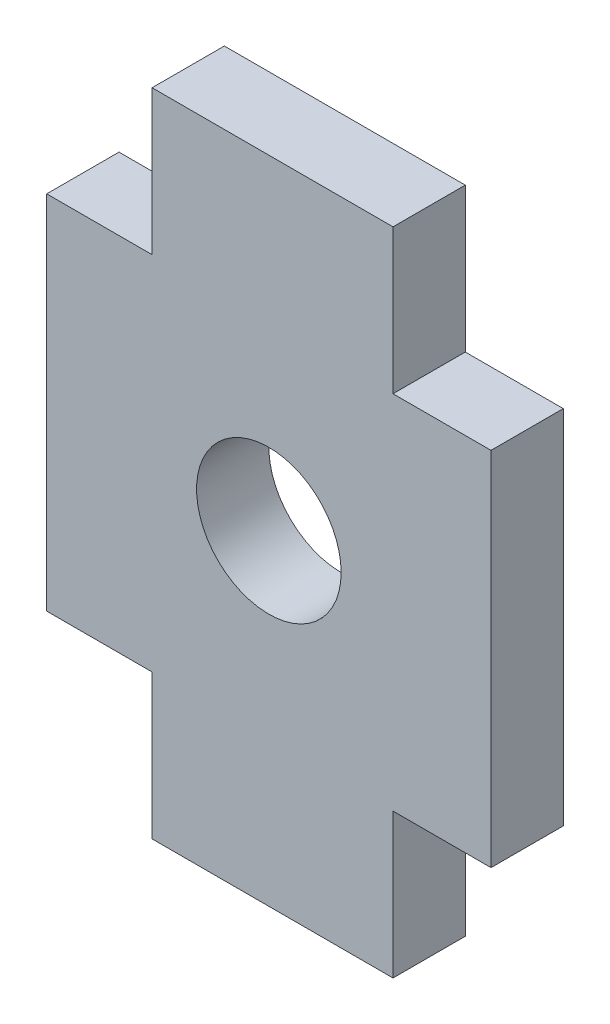
SolidWorks part; units mm, degrees
ref_plane "Front Plane" through (0, 0, 0) normal (0, 0, 1) x (1, 0, 0)
ref_plane "Top Plane" through (0, 0, 0) normal (0, 1, 0) x (1, 0, 0)
ref_plane "Right Plane" through (0, 0, 0) normal (1, 0, 0) x (0, 0, -1)
sketch "Sketch1" plane through (0, 0, 0) normal (0, 0, 1) x (1, 0, 0)
  line L2 (-211.4286, -75.763) -> (-211.4286, -105.763)
  line L4 (-174.5494, -75.763) -> (-174.5494, -105.763)
  line L6 (-202.6836, -69.763) -> (-202.6836, -63.763)
  line L7 (-202.6836, -63.763) -> (-182.6836, -63.763)
  line L8 (-182.6836, -69.763) -> (-182.6836, -63.763)
  line L14 (-211.4286, -75.763) -> (-202.6836, -75.763)
  line L16 (-202.6836, -69.763) -> (-202.6836, -75.763)
  line L18 (-182.6836, -69.763) -> (-182.6836, -75.763)
  line L19 (-182.6836, -75.763) -> (-174.5494, -75.763)
  line L21 (-182.6836, -105.763) -> (-174.5494, -105.763)
  line L22 (-182.6836, -111.763) -> (-182.6836, -105.763)
  line L23 (-202.6836, -111.763) -> (-202.6836, -105.763)
  line L24 (-211.4286, -105.763) -> (-202.6836, -105.763)
  line L25 (-182.6836, -111.763) -> (-182.6836, -117.763)
  line L26 (-202.6836, -117.763) -> (-182.6836, -117.763)
  line L27 (-202.6836, -111.763) -> (-202.6836, -117.763)
  circle A0 centre (-192.989, -90.763) radius 6
  dimension "D3" = 12
  dimension "D1" = 6
  dimension "D2" = 6
  dimension "D9" = 30
  dimension "D10" = 12
extrude "Boss-Extrude1" add sketch "Sketch1" along normal blind 6
